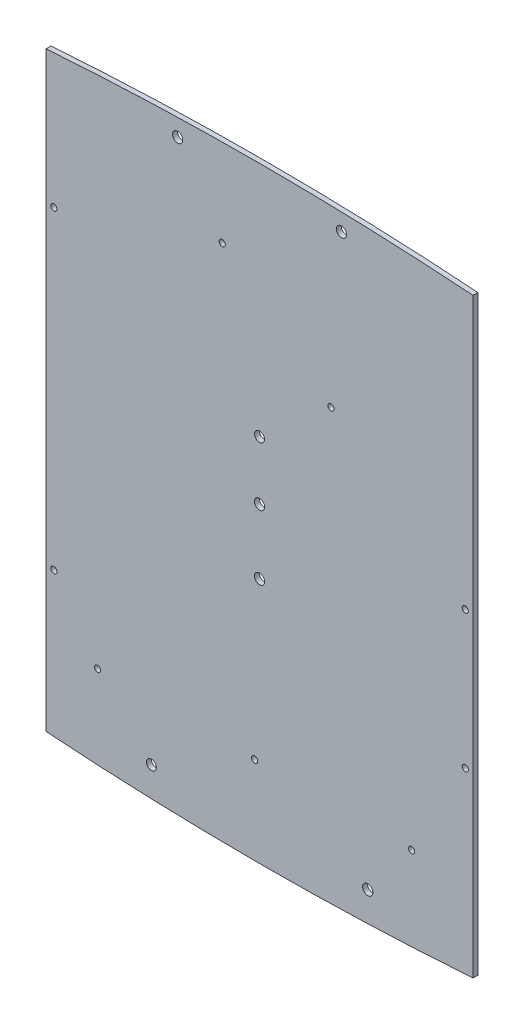
SolidWorks part; units mm, degrees
ref_plane "Front Plane" through (0, 0, 0) normal (0, 0, 1) x (1, 0, 0)
ref_plane "Top Plane" through (0, 0, 0) normal (0, 1, 0) x (1, 0, 0)
ref_plane "Right Plane" through (0, 0, 0) normal (1, 0, 0) x (0, 0, -1)
sketch "Sketch1" plane through (0, 0, 0) normal (0, 0, 1) x (1, 0, 0)
  line L2 (138.1125, 191.25) -> (138.1125, -191.25)
  line L3 (-138.1125, -191.25) -> (-138.1125, 191.25)
  circle A18 centre (46.1772, 82.55) radius 2
  circle A19 centre (53, 184.28) radius 3.3
  circle A20 centre (-24.13, 139.446) radius 2
  circle A21 centre (-133.096, 104.9366) radius 2
  circle A22 centre (-53, 184.28) radius 3.3
  circle A23 centre (0, 43) radius 3.2
  circle A24 centre (0, 5.15) radius 3.3
  circle A25 centre (0, -36.65) radius 3.3
  circle A26 centre (133.096, 12.7) radius 2
  circle A27 centre (133.096, -76.2) radius 2
  circle A28 centre (98.425, -139.446) radius 2
  circle A29 centre (70, -175.85) radius 3.3
  circle A30 centre (-3.175, -139.446) radius 2
  circle A31 centre (-133.096, -98.2634) radius 2
  circle A32 centre (-104.775, -139.446) radius 2
  circle A33 centre (-70, -175.85) radius 3.2
  arc A34 (-138.1125, -191.25) -> (138.1125, -191.25) centre (0, 1739.4965) ccw
  arc A35 (138.1125, 191.25) -> (-138.1125, 191.25) centre (0, -1739.4965) ccw
extrude "Extrude1" add sketch "Sketch1" along normal blind 3.175
